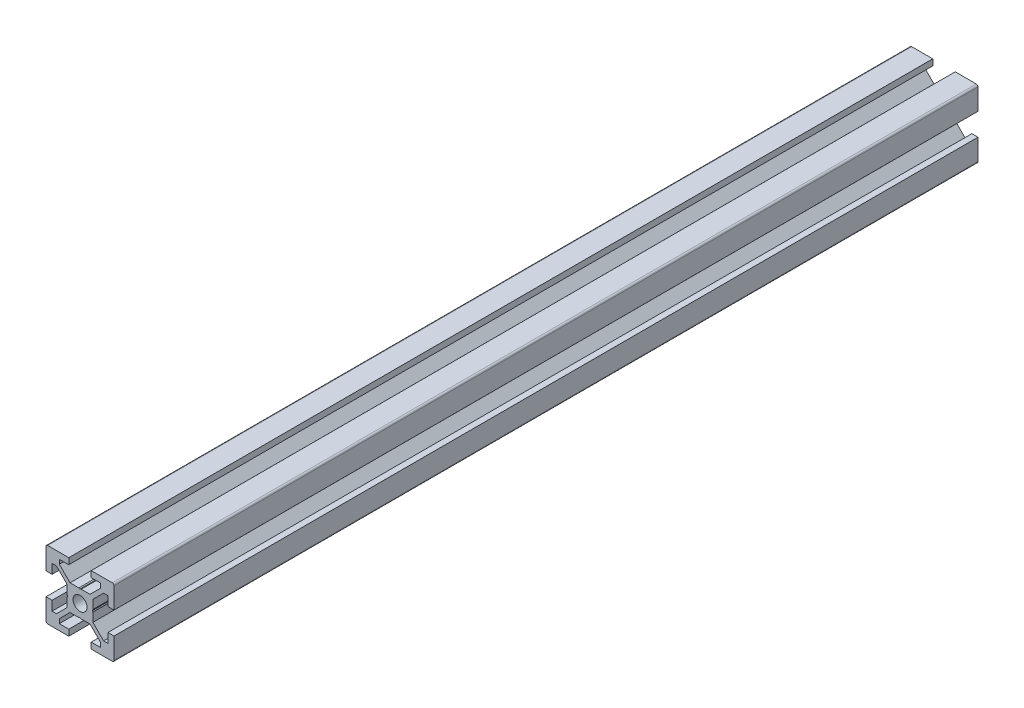
SolidWorks part; units mm, degrees
ref_plane "Front Plane" through (0, 0, 0) normal (0, 0, 1) x (1, 0, 0)
ref_plane "Top Plane" through (0, 0, 0) normal (0, 1, 0) x (1, 0, 0)
ref_plane "Right Plane" through (0, 0, 0) normal (1, 0, 0) x (0, 0, -1)
sketch "Sketch1" plane through (0, 0, 0) normal (0, 0, 1) x (1, 0, 0)
  line L0 (-3.3, 10) -> (-3.3, 8.2)
  line L1 (0, 0) -> (50000, 0) construction
  line L2 (-10, 3.3) -> (-10, 10)
  line L3 (-10, 10) -> (-3.3, 10)
  line L4 (0, 0) -> (0, 50000) construction
  line L5 (-10, -10) -> (10, 10) construction
  line L6 (-10, 10) -> (10, -10) construction
  line L7 (-2.9315, -3.78) -> (-0.34, -3.78)
  line L8 (-3.78, -2.9315) -> (-3.78, -0.34)
  line L9 (-2.9315, 3.78) -> (-0.34, 3.78)
  line L10 (3.78, -2.9315) -> (3.78, -0.34)
  line L11 (-3.78, -3.78) -> (3.78, 3.78) construction
  line L12 (-3.78, 3.78) -> (3.78, -3.78) construction
  line L13 (-6.08, 8.2) -> (-3.3, 8.2)
  line L14 (-8.2, 6.08) -> (-8.2, 3.3)
  line L15 (-8.2, 3.3) -> (-10, 3.3)
  line L16 (-8.2, 6.08) -> (-6.9285, 6.08)
  line L17 (-6.08, 8.2) -> (-6.08, 6.9285)
  line L18 (-6.9285, 6.08) -> (-3.78, 2.9315)
  line L19 (-6.08, 6.9285) -> (-2.9315, 3.78)
  line L20 (8.2, 6.08) -> (6.9285, 6.08)
  line L21 (8.2, 6.08) -> (8.2, 3.3)
  line L22 (8.2, 3.3) -> (10, 3.3)
  line L23 (10, 3.3) -> (10, 10)
  line L24 (10, 10) -> (3.3, 10)
  line L25 (3.3, 10) -> (3.3, 8.2)
  line L26 (6.08, 8.2) -> (3.3, 8.2)
  line L27 (6.08, 8.2) -> (6.08, 6.9285)
  line L28 (6.08, 6.9285) -> (2.9315, 3.78)
  line L29 (6.9285, 6.08) -> (3.78, 2.9315)
  line L30 (6.9285, -6.08) -> (3.78, -2.9315)
  line L31 (6.08, -6.9285) -> (2.9315, -3.78)
  line L32 (6.08, -8.2) -> (6.08, -6.9285)
  line L33 (6.08, -8.2) -> (3.3, -8.2)
  line L34 (3.3, -10) -> (3.3, -8.2)
  line L35 (10, -10) -> (3.3, -10)
  line L36 (10, -3.3) -> (10, -10)
  line L37 (8.2, -3.3) -> (10, -3.3)
  line L38 (8.2, -6.08) -> (8.2, -3.3)
  line L39 (8.2, -6.08) -> (6.9285, -6.08)
  line L40 (-6.08, -6.9285) -> (-2.9315, -3.78)
  line L41 (-6.9285, -6.08) -> (-3.78, -2.9315)
  line L42 (-6.08, -8.2) -> (-6.08, -6.9285)
  line L43 (-8.2, -6.08) -> (-6.9285, -6.08)
  line L44 (-8.2, -3.3) -> (-10, -3.3)
  line L45 (-8.2, -6.08) -> (-8.2, -3.3)
  line L46 (-6.08, -8.2) -> (-3.3, -8.2)
  line L47 (-10, -10) -> (-3.3, -10)
  line L48 (-10, -3.3) -> (-10, -10)
  line L49 (-3.3, -10) -> (-3.3, -8.2)
  line L50 (-0.34, 3.78) -> (0, 3.66)
  line L51 (0.34, 3.78) -> (0, 3.66)
  line L52 (0.34, 3.78) -> (2.9315, 3.78)
  line L53 (-3.78, -0.34) -> (-3.66, 0)
  line L54 (-3.78, 0.34) -> (-3.66, 0)
  line L55 (3.78, 0.34) -> (3.66, 0)
  line L56 (3.78, -0.34) -> (3.66, 0)
  line L57 (-0.34, -3.78) -> (0, -3.66)
  line L58 (0.34, -3.78) -> (0, -3.66)
  line L59 (3.78, 0.34) -> (3.78, 2.9315)
  line L60 (0.34, -3.78) -> (2.9315, -3.78)
  line L61 (-3.78, 0.34) -> (-3.78, 2.9315)
  circle A0 centre (0, 0) radius 2.05
  point P0 (0, 0)
  dimension "D3" = 4.1
  dimension "D1" = 20
  dimension "D2" = 20
  dimension "D4" = 7.56
  dimension "D5" = 6.7
  dimension "D6" = 6.7
  dimension "D7" = 0.6
  dimension "D8" = 3.92
  dimension "D9" = 0.34
  dimension "D10" = 0.12
extrude "Boss-Extrude1" add sketch "Sketch1" along normal blind 254
fillet "Fillet1" radius 0.5 4 edges at (-10, 10, 127) (-10, -10, 127) (10, -10, 127) (10, 10, 127)
